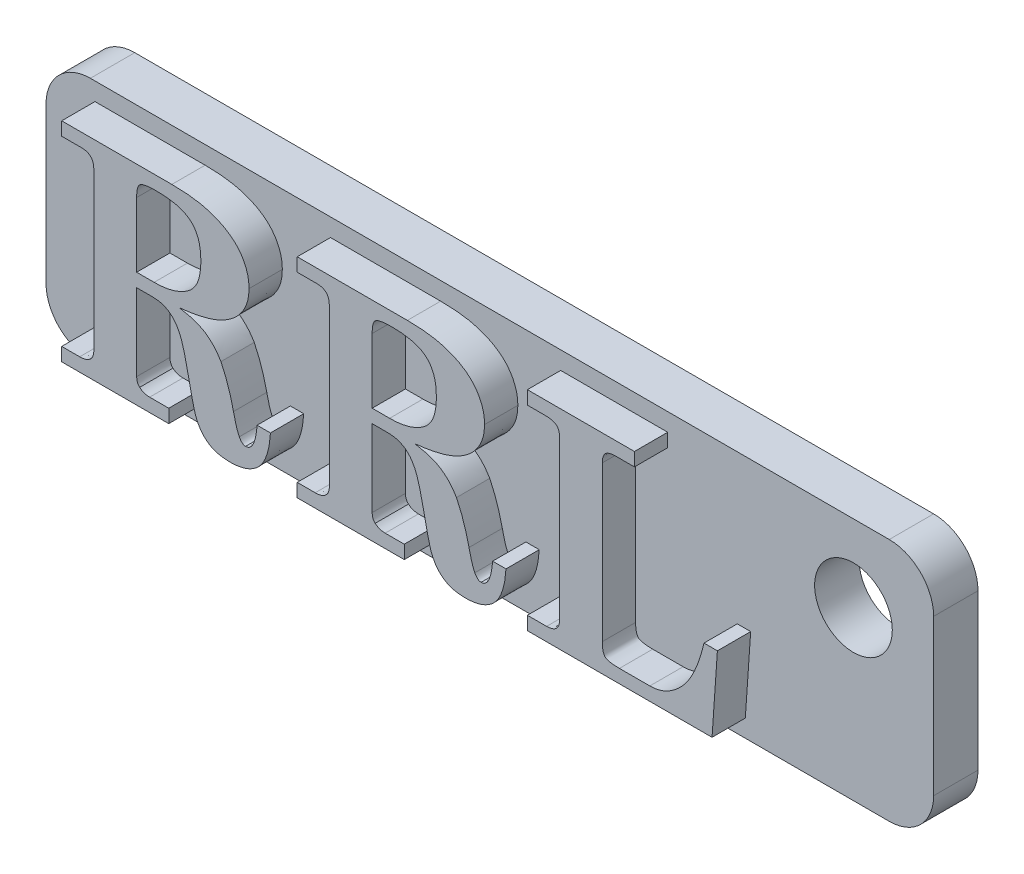
SolidWorks part; units mm, degrees
ref_plane "Front Plane" through (0, 0, 0) normal (0, 0, 1) x (1, 0, 0)
ref_plane "Top Plane" through (0, 0, 0) normal (0, 1, 0) x (1, 0, 0)
ref_plane "Right Plane" through (0, 0, 0) normal (1, 0, 0) x (0, 0, -1)
sketch "Sketch2" plane through (0, 0, 0) normal (0, 0, 1) x (1, 0, 0)
  line L1 (-18, 5.5) -> (18, 5.5)
  line L2 (-20, 3.5) -> (-20, -3.5)
  line L3 (-18, -5.5) -> (18, -5.5)
  line L4 (20, 3.5) -> (20, -3.5)
  line L5 (-20, 5.5) -> (20, -5.5) construction
  line L6 (-20, -5.5) -> (20, 5.5) construction
  arc A0 (18, 5.5) -> (20, 3.5) centre (18, 3.5) cw
  arc A1 (18, -5.5) -> (20, -3.5) centre (18, -3.5) ccw
  arc A2 (-20, -3.5) -> (-18, -5.5) centre (-18, -3.5) ccw
  arc A3 (-18, 5.5) -> (-20, 3.5) centre (-18, 3.5) ccw
  point P0 (0, 0)
  dimension "D3" = 2
  dimension "D1" = 40
  dimension "D2" = 11
extrude "Boss-Extrude2" add sketch "Sketch2" along normal blind 2
sketch "Sketch1" plane through (0, 0, 2) normal (0, 0, 1) x (1, 0, 0)
  line L0 (180, 540) -> (900, 540) construction
  text T0 "RRL" font "Century Schoolbook" height in points 36
extrude "Boss-Extrude1" add sketch "Sketch1" along normal blind 1.5
sketch "Sketch3" plane through (0, 0, 2) normal (0, 0, 1) x (1, 0, 0)
  circle A0 centre (16.3879, 2.034) radius 1.75
  point P2 (15.6661, 1.7609)
  point P3 (16.3879, 2.034)
  dimension "D1" = 3.5
extrude "Cut-Extrude1" cut sketch "Sketch3" against normal through all
